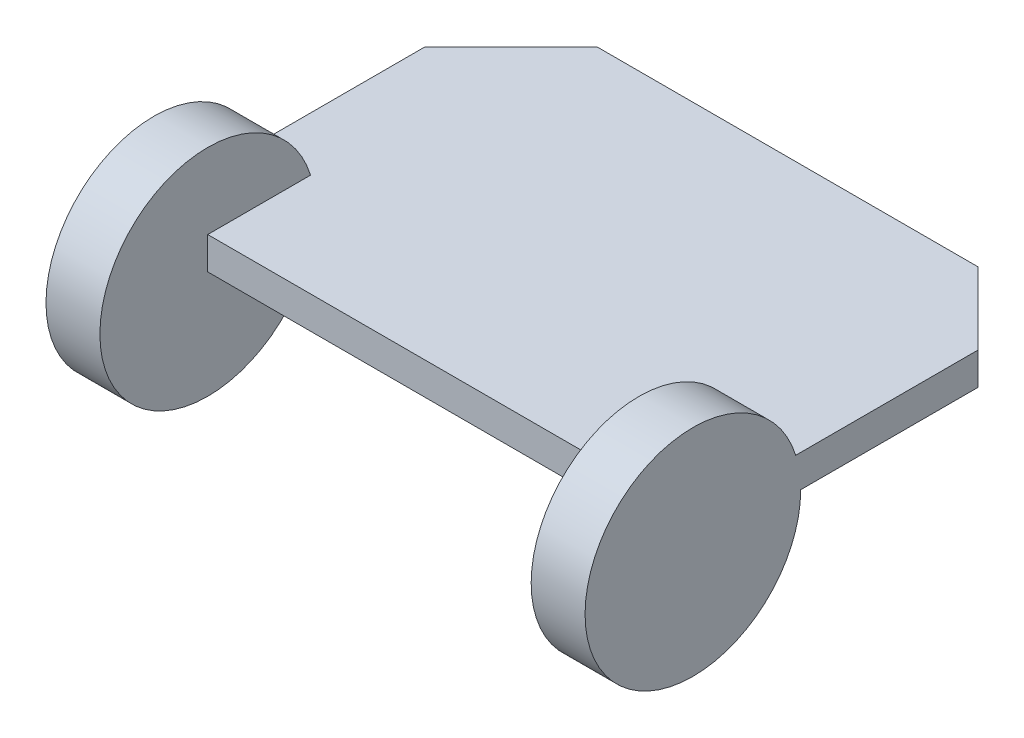
SolidWorks part; units mm, degrees
ref_plane "Front Plane" through (0, 0, 0) normal (0, 0, 1) x (1, 0, 0)
ref_plane "Top Plane" through (0, 0, 0) normal (0, 1, 0) x (1, 0, 0)
ref_plane "Right Plane" through (0, 0, 0) normal (1, 0, 0) x (0, 0, -1)
sketch "Sketch12" plane through (0, 0, 0) normal (0, 1, 0) x (1, 0, 0)
  line L0 (0, 25.137) -> (7.9923, 33.1293)
  line L1 (0, 0) -> (50, 0)
  line L2 (0, 0) -> (0, 25.137)
  line L3 (7.9923, 33.1293) -> (43.3154, 33.1293)
  line L4 (50, 0) -> (50, 26.4447)
  line L5 (43.3154, 33.1293) -> (50, 26.4447)
  line L7 (0, 0) -> (5, 0)
  line L8 (0, 0) -> (0, 20)
  line L9 (0, 20) -> (5, 20)
  line L10 (5, 0) -> (5, 20)
  line L11 (50, 0) -> (45, 0)
  line L12 (50, 0) -> (50, 20)
  line L13 (50, 20) -> (45, 20)
  line L14 (45, 0) -> (45, 20)
  point P1 (50, 33.1293)
  point P2 (0, 33.1293)
  point P15 (0, 0)
  point P16 (0, 0)
  point P17 (0, 0)
extrude "Boss-Extrude3" add sketch "Sketch12" along normal blind 3 contours L1 L14 L13 L4 L5 L3 L0 L2 L9 L10 | L14 L1 L4 L13 | L1 L10 L9 L2
sketch "Sketch13" plane through (0, 0, 0) normal (-1, 0, 0) x (0, 0, 1)
  circle A0 centre (0, 0) radius 10
extrude "Boss-Extrude4" add sketch "Sketch13" against normal blind 5
sketch "Sketch14" plane through (50, 0, 0) normal (1, 0, 0) x (0, 0, -1)
  circle A0 centre (0, 0) radius 10
extrude "Boss-Extrude6" add sketch "Sketch14" against normal blind 5
sketch "Bend-Lines1" [suppressed] plane through (0, 0, 0) normal (0, 1, 0) x (1, 0, 0)
sketch "Bounding-Box1" [suppressed] plane through (0, 0, 0) normal (0, 1, 0) x (1, 0, 0)
